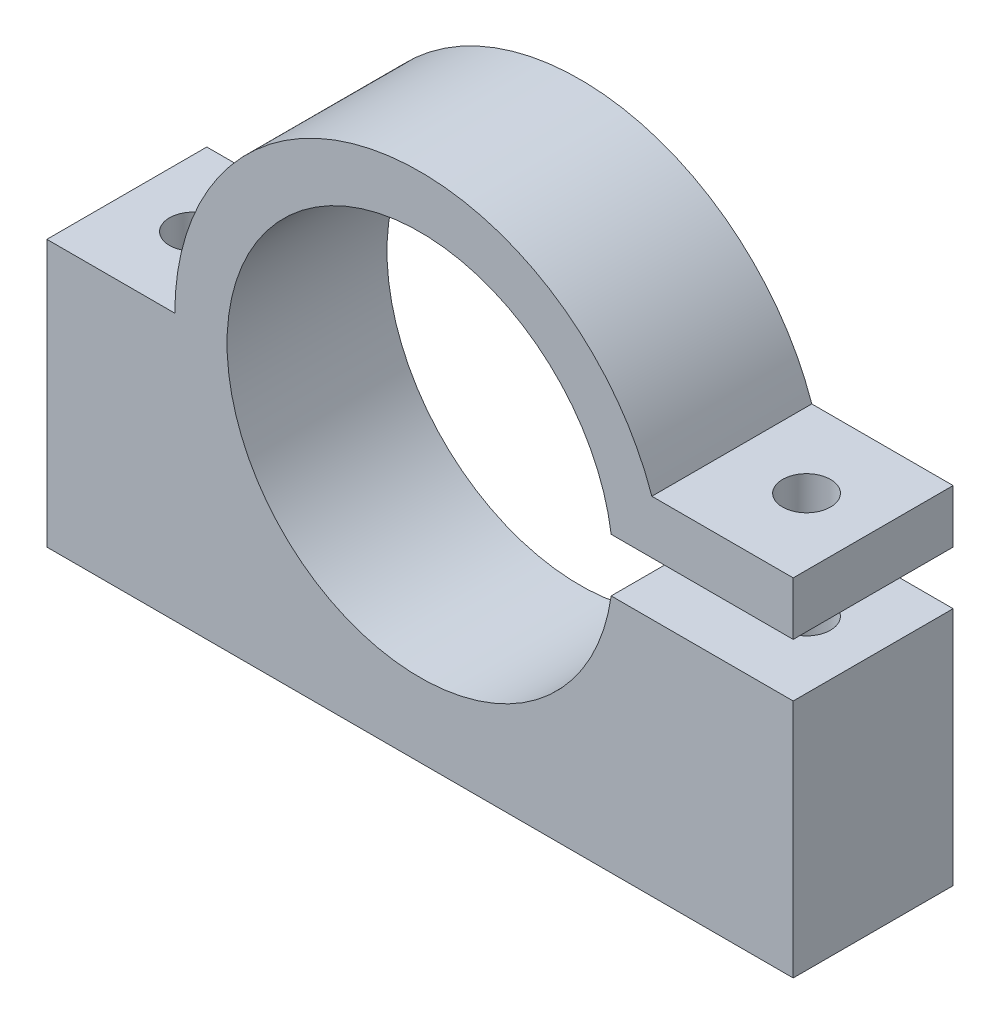
SolidWorks part; units mm, degrees
ref_plane "Ön Düzlem" through (0, 0, 0) normal (0, 0, 1) x (1, 0, 0)
ref_plane "Üst Düzlem" through (0, 0, 0) normal (0, 1, 0) x (1, 0, 0)
ref_plane "Sağ Düzlem" through (0, 0, 0) normal (1, 0, 0) x (0, 0, -1)
sketch "Sketch1" plane through (0, 0, 0) normal (0, 0, 1) x (1, 0, 0)
  line L0 (0, 0) -> (-18.1, 0)
  line L1 (35, 2.5) -> (35, 7.5)
  line L2 (35, 7.5) -> (21.7428, 7.5)
  line L3 (0, 0) -> (0, 5)
  line L4 (17.9265, 2.5) -> (35, 2.5)
  line L5 (35, 2.5) -> (35, 0)
  line L6 (35, 0) -> (35, -2.5)
  line L7 (35, -2.5) -> (17.9265, -2.5)
  line L8 (0, -5) -> (0, 0)
  line L9 (0, 0) -> (-35, 0)
  line L10 (35, -2.5) -> (35, -7.5)
  line L11 (-35, 0) -> (-35, -25)
  line L12 (-35, 0) -> (-35, -22.5)
  line L14 (35, -22.5) -> (35, -7.5)
  line L15 (-35, -25) -> (35, -25)
  line L16 (35, -25) -> (35, -22.5)
  arc A0 (17.9265, 2.5) -> (17.9265, -2.5) centre (0, 0) ccw
  arc A1 (21.7428, 7.5) -> (-23, 0) centre (0, 0) ccw
  dimension "D1" = 36.2
  dimension "D4" = 46
  dimension "D9" = 5
  dimension "D2" = 35
  dimension "D3" = 70
  dimension "D5" = 5
  dimension "D6" = 2.5
  dimension "D7" = 2.5
  dimension "D8" = 5
  dimension "D10" = 25
extrude "Boss-Extrude2" add sketch "Sketch1" along normal blind 15 contours A0 L9 L11 L15 L16 L14 L10 L7 | L2 A1 L9 A0 L4 L1
sketch "Sketch4" plane through (0, 0, 0) normal (0, 1, 0) x (1, 0, 0)
  line L0 (-28.75, -7.5) -> (28.75, -7.5)
  circle A0 centre (-28.75, -7.5) radius 2.25
  circle A1 centre (28.75, -7.5) radius 2.25
  dimension "D1" = 4.5
  dimension "D3" = 4.5
  dimension "D2" = 57.5
extrude "Cut-Extrude3" cut sketch "Sketch4" against normal through all both and the other way through all
